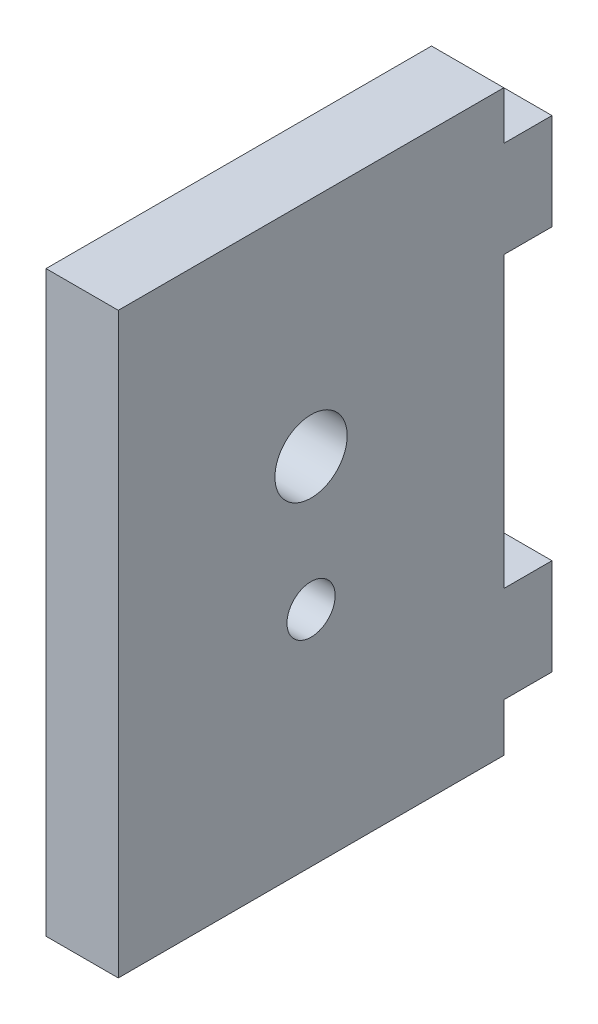
SolidWorks part; units mm, degrees
ref_plane "Front Plane" through (0, 0, 0) normal (1, 0, 0) x (0, 1, 0)
ref_plane "Top Plane" through (0, 0, 0) normal (0, 0, 1) x (0, 1, 0)
ref_plane "Right Plane" through (0, 0, 0) normal (0, 1, 0) x (-1, 0, 0)
sketch "Sketch1" plane through (0, 0, 0) normal (1, 0, 0) x (0, 1, 0)
  line L1 (0, 0) -> (76.2, 0)
  line L2 (0, 0) -> (0, 50.8)
  line L3 (0, 50.8) -> (76.2, 50.8)
  line L4 (76.2, 0) -> (76.2, 50.8)
  dimension "D1" = 76.2
  dimension "D2" = 50.8
extrude "Boss-Extrude1" add sketch "Sketch1" along normal blind 9.525
sketch "Sketch3" plane through (9.525, 0, 0) normal (1, 0, 0) x (0, 1, 0)
  line L0 (38.1, 50.8) -> (38.1, 0) construction
  line L1 (76.2, 50.8) -> (0, 50.8) construction
  line L2 (0, 0) -> (76.2, 0) construction
  line L3 (0, 25.4) -> (76.2, 25.4) construction
  line L4 (0, 50.8) -> (0, 0) construction
  line L5 (76.2, 0) -> (76.2, 50.8) construction
  circle A0 centre (29.3688, 25.4) radius 3.175
  circle A1 centre (46.8313, 25.4) radius 4.7625
  point P16 (0, 0)
  dimension "D1" = 9.525
  dimension "D2" = 6.35
  dimension "D3" = 17.4625
  dimension "D4" = 8.7312
extrude "Cut-Extrude1" cut sketch "Sketch3" against normal through all
sketch "Sketch4" plane through (0, 0, 0) normal (0, 0, -1) x (1, 0, 0)
  line L0 (9.525, 0) -> (9.525, -76.2) construction
  line L1 (9.525, -6.35) -> (0, -6.35)
  line L2 (9.525, -6.35) -> (9.525, -19.05)
  line L3 (9.525, -19.05) -> (0, -19.05)
  line L4 (0, -6.35) -> (0, -19.05)
  line L5 (0, 0) -> (0, -76.2) construction
  line L6 (9.525, -76.2) -> (0, -76.2) construction
  line L7 (9.525, -57.15) -> (0, -57.15)
  line L8 (9.525, -57.15) -> (9.525, -69.85)
  line L9 (9.525, -69.85) -> (0, -69.85)
  line L10 (0, -57.15) -> (0, -69.85)
  line L11 (9.525, 0) -> (0, 0) construction
  dimension "D1" = 12.7
  dimension "D2" = 12.7
  dimension "D3" = 6.35
  dimension "D4" = 6.35
  dimension "D5" = 9.525
  dimension "D6" = 9.525
extrude "Boss-Extrude2" add sketch "Sketch4" along normal blind 6.35
equation "\"shaft_len\"= 1in"
equation "\"ouput_shaft_d\"= 0.25"
equation "\"input_shaft_d\" = 0.125in"
equation "\"pinion_pitch\"= 3 / 8in"
equation "\"gear_pitch\"= 1in"
equation "\"pitch_tot\"= \"pinion_pitch\" + \"gear_pitch\""
equation "\"sleeve_len\"= 3 / 8in"
equation "\"pinion_sleeve_d\"= 1 / 4in"
equation "\"gear_sleeve_d\"= 3 / 8in"
equation "\"D1@Boss-Extrude1\"=\"sleeve_len\""
equation "\"D1@Sketch3\"=\"gear_sleeve_d\""
equation "\"D2@Sketch3\"=\"pinion_sleeve_d\""
equation "\"D3@Sketch3\"=\"pitch_tot\"*.5"
equation "\"D4@Sketch3\"=\"pitch_tot\"*.5*.5"
equation "\"D1@Sketch4\"=0.5"
equation "\"D2@Sketch4\"=0.5"
